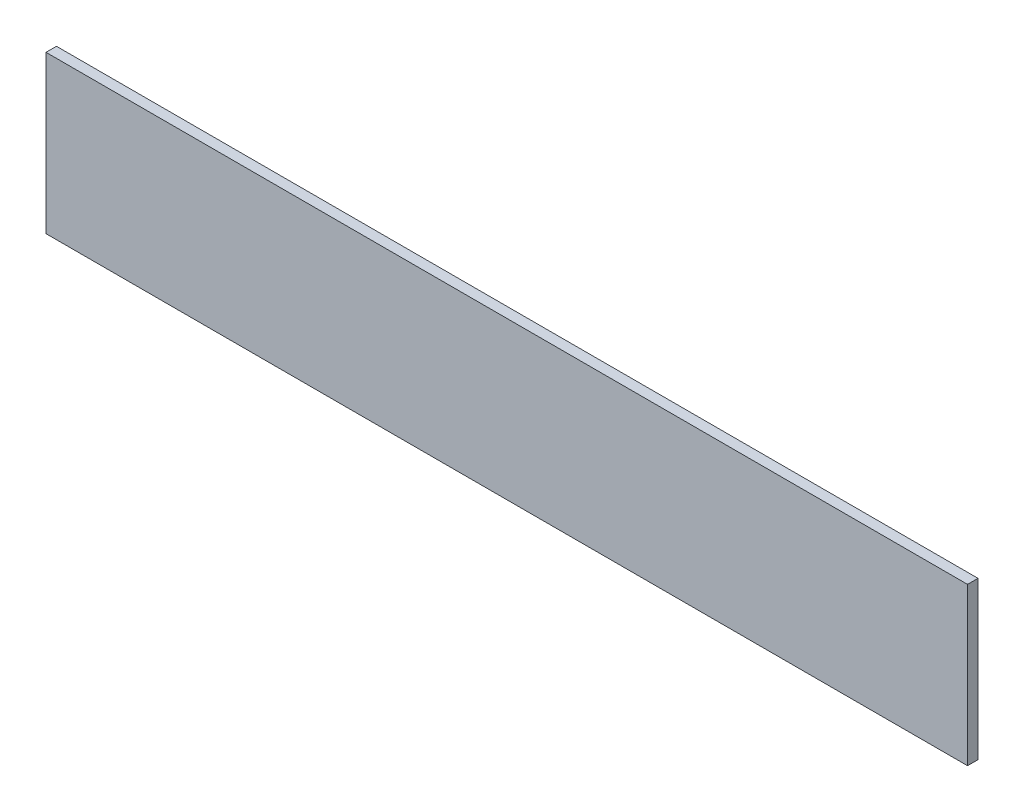
SolidWorks part; units mm, degrees
ref_plane "正面" through (0, 0, 0) normal (0, 0, 1) x (1, 0, 0)
ref_plane "平面" through (0, 0, 0) normal (0, 1, 0) x (1, 0, 0)
ref_plane "右側面" through (0, 0, 0) normal (1, 0, 0) x (0, 0, -1)
sketch "ｽｹｯﾁ1" plane through (0, 0, 0) normal (0, 0, 1) x (1, 0, 0)
  line L1 (-44, -7.5) -> (44, -7.5)
  line L2 (-44, -7.5) -> (-44, 7.5)
  line L3 (-44, 7.5) -> (44, 7.5)
  line L4 (44, -7.5) -> (44, 7.5)
  line L5 (-44, -7.5) -> (44, 7.5) construction
  line L6 (-44, 7.5) -> (44, -7.5) construction
  point P0 (0, 0)
  dimension "D1" = 15
  dimension "D2" = 88
extrude "ﾎﾞｽ - 押し出し1" add sketch "ｽｹｯﾁ1" along normal blind 1
